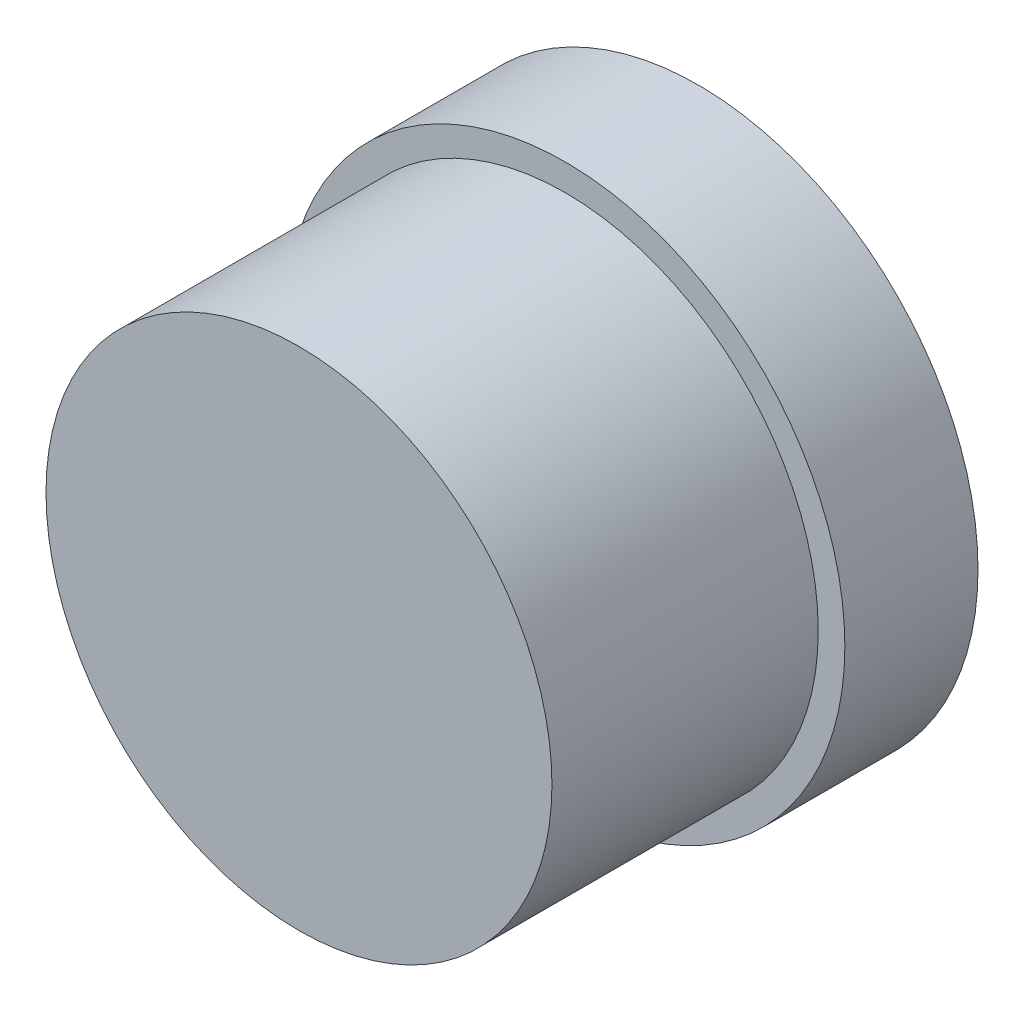
SolidWorks part; units mm, degrees
material "6061 Alloy"
ref_plane "Front" through (0, 0, 0) normal (0, 0, 1) x (1, 0, 0)
ref_plane "Top" through (0, 0, 0) normal (0, 1, 0) x (1, 0, 0)
ref_plane "Right" through (0, 0, 0) normal (1, 0, 0) x (0, 0, -1)
sketch "Sketch2" plane through (0, 0, 0) normal (0, 0, 1) x (1, 0, 0)
  circle A0 centre (0, 0) radius 210
  dimension "D1" = 420
extrude "Boss-Extrude1" add sketch "Sketch2" along normal blind 100
sketch "Sketch3" plane through (0, 0, 100) normal (0, 0, 1) x (1, 0, 0)
  circle A0 centre (0, 0) radius 190
  dimension "D1" = 380
extrude "Boss-Extrude2" add sketch "Sketch3" along normal blind 200
